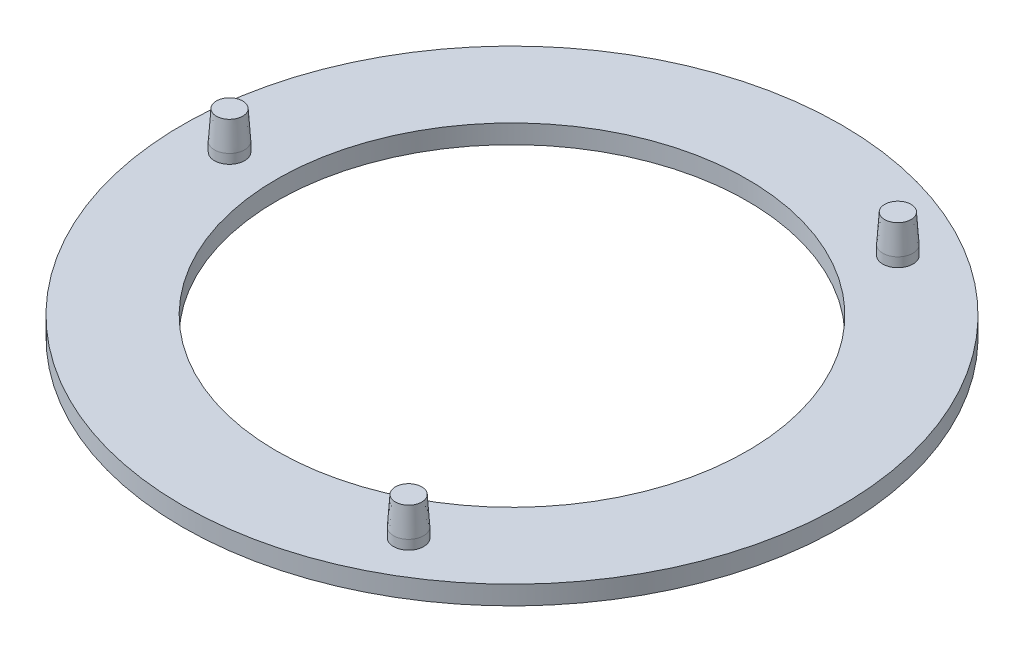
SolidWorks part; units mm, degrees
ref_plane "Front Plane" through (0, 0, 0) normal (0, 0, 1) x (1, 0, 0)
ref_plane "Top Plane" through (0, 0, 0) normal (0, 1, 0) x (1, 0, 0)
ref_plane "Right Plane" through (0, 0, 0) normal (1, 0, 0) x (0, 0, -1)
sketch "Sketch1" plane through (0, 0, 0) normal (0, 1, 0) x (1, 0, 0)
  circle A0 centre (0, 0) radius 31.75
  circle A1 centre (0, 0) radius 44.45
  dimension "D1" = 63.5
  dimension "D2" = 88.9
extrude "Boss-Extrude1" add sketch "Sketch1" along normal blind 2.54
sketch "Sketch2" plane through (0, 0, 0) normal (0, 0, 1) x (1, 0, 0)
  line L0 (0, 6.2846) -> (0, -3.885) construction
sketch "Sketch4" plane through (0, 0, 0) normal (0, 0, 1) x (1, 0, 0)
  line L0 (-38.1, 2.54) -> (-38.1, 7.62)
  line L1 (44.45, 2.54) -> (-44.45, 2.54) construction
  line L2 (-38.1, 7.62) -> (-39.878, 7.62)
  line L3 (-39.878, 7.62) -> (-40.132, 3.81)
  line L4 (-40.132, 3.81) -> (-40.132, 2.54)
  line L5 (-40.132, 2.54) -> (-38.1, 2.54)
  line L6 (0, 6.2846) -> (0, -3.885) construction
  dimension "D1" = 38.1
  dimension "D2" = 2.032
  dimension "D3" = 1.27
  dimension "D4" = 1.778
  dimension "D5" = 5.08
revolve "Revolve1" add sketch "Sketch4" angle 360 about L0
pattern_circular "CirPattern1" count 3 every 120 about axis through (0, 0, 0) along (0, 1, 0) of "Revolve1"
